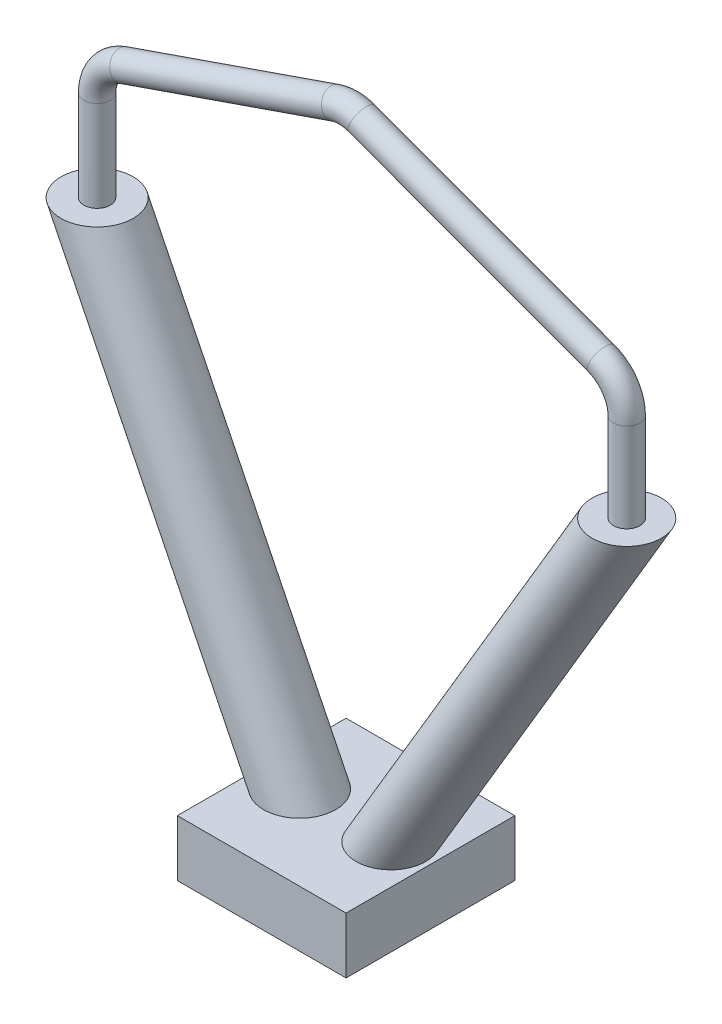
SolidWorks part; units mm, degrees
ref_plane "Alzado" through (0, 0, 0) normal (0, 0, 1) x (1, 0, 0)
ref_plane "Planta" through (0, 0, 0) normal (0, 1, 0) x (1, 0, 0)
ref_plane "Vista lateral" through (0, 0, 0) normal (1, 0, 0) x (0, 0, -1)
sketch "Croquis1" plane through (0, 0, 0) normal (0, 1, 0) x (1, 0, 0)
  line L1 (-150, 150) -> (150, 150)
  line L2 (-150, 150) -> (-150, -150)
  line L3 (-150, -150) -> (150, -150)
  line L4 (150, 150) -> (150, -150)
  line L5 (-150, 150) -> (150, -150) construction
  line L6 (-150, -150) -> (150, 150) construction
  point P0 (0, 0)
  dimension "D1" = 300
  dimension "D2" = 300
extrude "Saliente-Extruir1" add sketch "Croquis1" along normal blind 100
sketch "Croquis2" plane through (0, 100, 0) normal (0, 1, 0) x (1, 0, 0)
  circle A0 centre (79.7197, 0) radius 61.7578
  point P2 (100.0152, 0)
  point P3 (79.7197, 0)
sketch3d "Croquis3D1"
  line L0 (79.7197, 100, 0) -> (499.0174, 807.6577, 0)
  point P3 (499.0174, 807.6577, 0)
sweep "Barrer1" add profiles "Croquis2" path "Croquis3D1"
sketch "Croquis3" plane through (0, 100, 0) normal (0, 1, 0) x (1, 0, 0)
  circle A0 centre (-82.5763, 0) radius 64.1383
  point P2 (-82.5763, 0)
sketch3d "Croquis3D2"
  line L0 (-82.5763, 100, 0) -> (-442.6526, 830.3663, 0)
  point P3 (-442.6526, 830.3663, 0)
sweep "Barrer2" add profiles "Croquis3" path "Croquis3D2"
ref_plane "Plano1" through (0, 520, 0) normal (0, 1, 0) x (1, 0, 0)
sketch "Croquis5" plane through (0, 807.6577, 0) normal (0, 1, 0) x (1, 0, 0)
  line L0 (79.7197, 0) -> (499.0174, 0) construction
  circle A0 centre (499.0174, 0) radius 23.4986
sketch3d "Croquis3D4"
  line L0 (499.0174, 807.6577, 0) -> (499.0174, 965.7432, 0)
  line L1 (453.1706, 1031.4442, 0) -> (27.9929, 1187.7493, 0)
  line L2 (-442.6526, 830.3663, 0) -> (-442.6526, 991.7492, 0)
  line L3 (-395.5464, 1057.8996, 0) -> (-19.0541, 1188.1987, 0)
  arc A0 (-442.6526, 991.7492, 0) -> (-395.5464, 1057.8996, 0) centre (-372.6526, 991.7492, 0) ccw
  arc A1 (27.9929, 1187.7493, 0) -> (-19.0541, 1188.1987, 0) centre (3.8397, 1122.0483, 0) ccw
  arc A2 (499.0174, 965.7432, 0) -> (453.1706, 1031.4442, 0) centre (429.0174, 965.7432, 0) ccw
  point P9 (-442.6526, 1041.5968, 0)
  point P10 (-372.6526, 991.7492, -70)
  point P13 (4.5496, 1196.3676, 0)
  point P14 (3.8397, 1122.0483, 70)
  point P17 (499.0174, 1014.5899, 0)
  point P18 (429.0174, 965.7432, 70)
  dimension "D1" = 70
sweep "Barrer4" add profiles "Croquis5" path "Croquis3D4"
